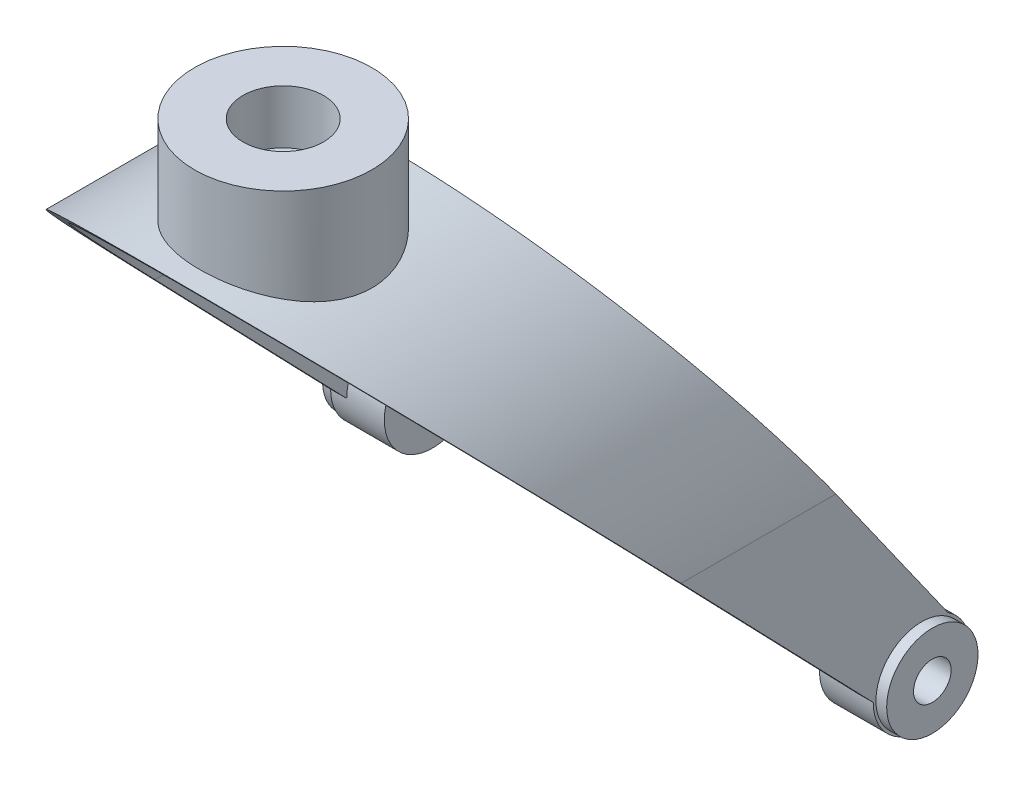
SolidWorks part; units mm, degrees
material "Hierro dúctil (SN)"
ref_plane "Alzado" through (0, 0, 0) normal (0, 0, 1) x (1, 0, 0)
ref_plane "Planta" through (0, 0, 0) normal (0, 1, 0) x (1, 0, 0)
ref_plane "Vista lateral" through (0, 0, 0) normal (1, 0, 0) x (0, 0, -1)
sketch "Croquis1" plane through (0, 0, 0) normal (0, 0, 1) x (1, 0, 0)
  line L0 (69.6411, 46.5431) -> (69.6411, -23.5367)
  line L2 (-28.3589, 46.4633) -> (-28.3589, -23.5367)
  line L4 (66.6411, 46.4633) -> (66.6411, -23.5367)
  line L5 (-31.3589, 46.5431) -> (-31.3589, -23.5367)
  line L6 (-31.3589, -23.5367) -> (-28.3589, -23.5367)
  line L7 (66.6411, -23.5367) -> (69.6411, -23.5367)
  arc A0 (66.6411, 46.4633) -> (-28.3589, 46.4633) centre (19.1411, 43.8938) ccw
  arc A1 (69.6411, 46.5431) -> (-31.3589, 46.5431) centre (19.1411, 43.8938) ccw
  point P5 (19.1411, 91.4633)
  dimension "D1" = 115
  dimension "D2" = 95
  dimension "D4" = 115
  dimension "D3" = 3
extrude "Saliente-Extruir1" add sketch "Croquis1" along normal blind 100
sketch "Croquis2" plane through (69.6411, 0, 0) normal (1, 0, 0) x (0, 0, -1)
  line L0 (-100, 94.4633) -> (-18, 9.4633)
  line L1 (0, -23.5367) -> (0, 46.5431) construction
  line L2 (-60, 94.4633) -> (0, 9.4633)
  line L3 (0, 9.4633) -> (-18, 9.4633) construction
  line L4 (0, 94.4633) -> (-100, 94.4633) construction
  line L5 (-60, 94.4633) -> (0, 94.4633)
  line L6 (0, 46.5431) -> (0, 94.4633) construction
  line L8 (0, 6.9633) -> (0, -23.5367)
  line L9 (0, -23.5367) -> (-100, -23.5367)
  line L10 (-100, -23.5367) -> (-100, 94.4633)
  line L11 (0, 9.4633) -> (-18, 9.4633)
  line L12 (0, 6.9633) -> (15.1725, 86.125)
  line L13 (15.1725, 86.125) -> (0, 94.4633)
  dimension "D1" = 40
  dimension "D2" = 18
  dimension "D3" = 85
extrude "Cortar-Extruir1" cut sketch "Croquis2" against normal blind 141
sketch "Croquis3" plane through (69.6411, 0, 0) normal (1, 0, 0) x (0, 0, -1)
  line L0 (0, 9.4633) -> (-18, 9.4633) construction
  circle A0 centre (-9, 9.4633) radius 9
extrude "Saliente-Extruir2" add sketch "Croquis3" against normal blind 10
ref_plane "Plano1" through (19.1411, 0, 0) normal (1, 0, 0) x (0, 0, -1)
sketch "Croquis4" plane through (69.6411, 0, 0) normal (1, 0, 0) x (0, 0, -1)
  circle A0 centre (-9, 9.4633) radius 8.5
  dimension "D1" = 17
extrude "Saliente-Extruir3" add sketch "Croquis4" along normal blind 2
sketch "Croquis5" plane through (71.6411, 0, 0) normal (1, 0, 0) x (0, 0, -1)
  circle A0 centre (-9, 9.4633) radius 3.5
  dimension "D1" = 7
extrude "Cortar-Extruir2" cut sketch "Croquis5" against normal blind 14
mirror "Simetría1" about plane through (19.1411, 0, 0) normal (1, 0, 0) of "Cortar-Extruir2", "Saliente-Extruir2", "Saliente-Extruir3"
sketch "Croquis6" plane through (0, 3.1471, -4.4584) normal (0, 0.5767, -0.817) x (-1, 0, 0)
  line L0 (25.1489, 18.1115) -> (28.3589, 18.1115)
  line L1 (-66.6411, 18.1115) -> (-67.5344, 18.1115)
  line L2 (-66.6411, 18.1115) -> (-66.6411, 53.0206)
  line L4 (28.3589, 18.1115) -> (28.3589, 53.0206)
  line L5 (-19.1411, 111.7744) -> (-19.1411, 81.7744) construction
  line L6 (-66.6411, 18.1115) -> (-69.6411, 18.1115)
  line L7 (28.3589, 18.1115) -> (31.3589, 18.1115)
  arc A0 (28.3589, 53.0206) -> (-66.6411, 53.0206) centre (-19.1411, 28.1636) ccw
  ellipse E0 centre (-19.1411, 49.8755) end of major axis (-19.1411, -8.3513) minor radius 47.5694 (28.3589, 53.0206) -> (-66.6411, 53.0206) ccw construction
  ellipse E1 centre (-19.1411, 49.8755) end of major axis (-19.1411, -12.0234) minor radius 50.5694 (31.3589, 53.1183) -> (-69.6411, 53.1183) ccw construction
  ellipse E2 centre (-19.1411, 49.8755) end of major axis (-19.1411, -12.0234) minor radius 50.5694 (31.3589, 53.1183) -> (-69.6411, 53.1183) ccw
  line M7 (28.3589, 18.1115) -> (31.3589, 18.1115)
  line M8 (31.3589, 18.1115) -> (31.3589, 53.1183)
  ellipse M9 centre (-19.1411, 49.8755) end of major axis (-19.1411, -12.0234) minor radius 50.5694 (31.3589, 53.1183) -> (-69.6411, 53.1183) ccw
  line M10 (-69.6411, 53.1183) -> (-69.6411, 18.1115)
  line M11 (-69.6411, 18.1115) -> (-66.6411, 18.1115)
  line M12 (-66.6411, 18.1115) -> (-66.6411, 53.0206)
  ellipse M13 centre (-19.1411, 49.8755) end of major axis (-19.1411, -8.3513) minor radius 47.5694 (-66.6411, 53.0206) -> (28.3589, 53.0206) cw
  line M14 (28.3589, 53.0206) -> (28.3589, 18.1115)
  dimension "D1" = 30
extrude "Saliente-Extruir5" add sketch "Croquis6" along normal mid plane 2 contours L5 E2 M10 M11 M12 M13 | L5 M9 M13 M14 M7 M8 | L5 A0 M13 | L5 A0 M13
sketch "Croquis8" plane through (0, 0, 0) normal (0, 0, 1) x (1, 0, 0)
  line L0 (-31.3589, 46.5431) -> (-43.9952, 50.4056)
  line L1 (-43.9952, 50.4056) -> (-32.9359, 104.8004)
  line L2 (-32.9359, 104.8004) -> (86.3269, 97.4644)
  line L3 (86.3269, 97.4644) -> (84.8597, 44.645)
  line L4 (84.8597, 44.645) -> (69.6411, 46.5431)
  arc A0 (-31.3589, 46.5431) -> (69.6411, 46.5431) centre (19.1411, 43.8938) cw
  arc A1 (69.6411, 46.5431) -> (-31.3589, 46.5431) centre (19.1411, 43.8938) ccw construction
  arc A2 (69.6411, 46.5431) -> (-31.3589, 46.5431) centre (19.1411, 43.8938) ccw
sketch "Croquis10" plane through (0, 14.7965, 10.4446) normal (0, -0.817, -0.5767) x (1, 0, 0)
  line L1 (69.6411, -6.4573) -> (66.6411, -6.4573)
  line L2 (69.6411, -6.4573) -> (69.6411, -5.4573)
  line L3 (69.6411, -5.4573) -> (66.6411, -5.4573)
  line L4 (66.6411, -6.4573) -> (66.6411, -5.4573)
ref_plane "Plano2" through (0, 95, 0) normal (0, 1, 0) x (1, 0, 0)
sketch "Croquis11" plane through (0, 95, 0) normal (0, 1, 0) x (1, 0, 0)
  line L0 (21.175, -58.7471) -> (21.175, -99.9605) construction
  circle A0 centre (21.175, -79.3538) radius 16.5
  ellipse E0 centre (19.1411, -23.0799) end of major axis (-31.4284, -23.0799) minor radius 35.6961 (69.6411, -21.2098) -> (-31.3589, -24.95) ccw construction
  ellipse E1 centre (19.1411, -51.2154) end of major axis (-31.4284, -51.2154) minor radius 48.7846 (-31.3589, -53.7711) -> (69.6411, -53.7711) ccw construction
  dimension "D1" = 33
extrude "Saliente-Extruir7" add sketch "Croquis11" against normal up to surface (0.5777 mm away)
sketch "Croquis12" plane through (0, 95, 0) normal (0, 1, 0) x (1, 0, 0)
  circle A0 centre (21.175, -79.3538) radius 16.5
extrude "Saliente-Extruir8" add sketch "Croquis12" along normal blind 15
sketch "Croquis13" plane through (0, 110, 0) normal (0, 1, 0) x (1, 0, 0)
  circle A0 centre (21.175, -79.3538) radius 7.5
  dimension "D1" = 15
extrude "Cortar-Extruir5" cut sketch "Croquis13" against normal blind 10
extrude "Cortar-Extruir6" cut sketch "Croquis8" along normal up to vertex contours L0 A0 L4 L3 L2 L1
sketch "Croquis17" plane through (0, 14.7965, 10.4446) normal (0, -0.817, -0.5767) x (1, 0, 0)
  line L1 (-28.3589, -5.4573) -> (-31.3589, -5.4573)
  line L2 (-28.3589, -5.4573) -> (-28.3589, -6.4573)
  line L3 (-28.3589, -6.4573) -> (-31.3589, -6.4573)
  line L4 (-31.3589, -5.4573) -> (-31.3589, -6.4573)
extrude "Saliente-Extruir9" add sketch "Croquis17" along normal up to surface up to face at (-29.8589, 11.5834, 10.4965)
mirror "Simetría2" about plane through (19.1411, 0, 0) normal (1, 0, 0) of "Saliente-Extruir9"
